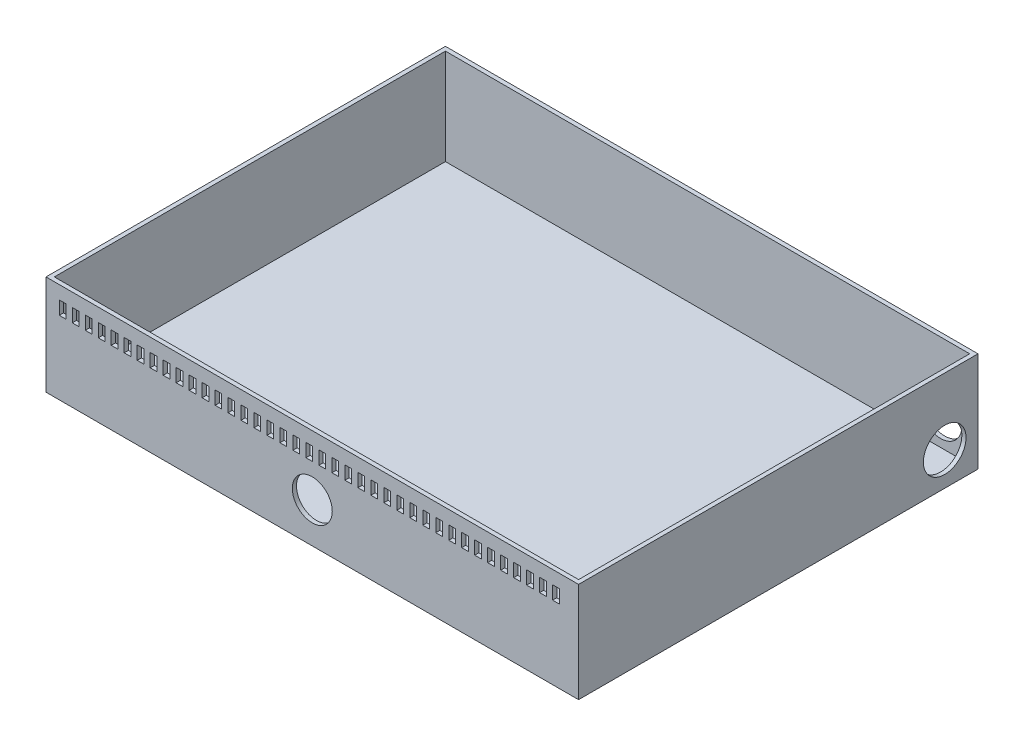
SolidWorks part; units mm, degrees
ref_plane "Front Plane" through (0, 0, 0) normal (0, 0, 1) x (1, 0, 0)
ref_plane "Top Plane" through (0, 0, 0) normal (0, 1, 0) x (1, 0, 0)
ref_plane "Right Plane" through (0, 0, 0) normal (1, 0, 0) x (0, 0, -1)
sketch "Sketch1" plane through (0, 0, 0) normal (0, 1, 0) x (1, 0, 0)
  line L1 (-101.6, -76.2) -> (101.6, -76.2)
  line L2 (-101.6, -76.2) -> (-101.6, 76.2)
  line L3 (-101.6, 76.2) -> (101.6, 76.2)
  line L4 (101.6, -76.2) -> (101.6, 76.2)
  line L5 (-101.6, -76.2) -> (101.6, 76.2) construction
  line L6 (-101.6, 76.2) -> (101.6, -76.2) construction
  point P0 (0, 0)
  dimension "D1" = 203.2
  dimension "D2" = 152.4
extrude "Boss-Extrude1" add sketch "Sketch1" along normal blind 38.1
sketch "Sketch2" plane through (0, 38.1, 0) normal (0, 1, 0) x (1, 0, 0)
  line L0 (-101.6, 76.2) -> (-101.6, -76.2) construction
  line L1 (-100.0125, -74.6125) -> (100.0125, -74.6125)
  line L2 (-100.0125, -74.6125) -> (-100.0125, 74.6125)
  line L3 (-100.0125, 74.6125) -> (100.0125, 74.6125)
  line L4 (100.0125, -74.6125) -> (100.0125, 74.6125)
  line L5 (-100.0125, -74.6125) -> (100.0125, 74.6125) construction
  line L6 (-100.0125, 74.6125) -> (100.0125, -74.6125) construction
  line L7 (101.6, 76.2) -> (-101.6, 76.2) construction
  line L8 (-101.6, -76.2) -> (101.6, -76.2) construction
  point P0 (0, 0)
  dimension "D1" = 1.5875
  dimension "D2" = 1.5875
  dimension "D3" = 1.5875
extrude "Cut-Extrude1" cut sketch "Sketch2" against normal blind 36.5125
sketch "Sketch3" plane through (0, 0, 76.2) normal (0, 0, 1) x (1, 0, 0)
  line L8 (-101.6, 38.1) -> (-101.6, 0) construction
  line L9 (-96.52, 33.02) -> (-93.98, 33.02)
  line L10 (-96.52, 33.02) -> (-96.52, 27.94)
  line L11 (-96.52, 27.94) -> (-93.98, 27.94)
  line L12 (-93.98, 33.02) -> (-93.98, 27.94)
  line L13 (-101.6, 38.1) -> (101.6, 38.1) construction
  dimension "D1" = 5.08
  dimension "D3" = 5.08
  dimension "D5" = 2.54
  dimension "D6" = 5.08
extrude "Cut-Extrude2" cut sketch "Sketch3" against normal blind 7.62
pattern_linear "LPattern1" count 39 spacing 4.953 along (1, 0, 0) of "Cut-Extrude2"
sketch "Sketch4" plane through (0, 0, 76.2) normal (0, 0, 1) x (1, 0, 0)
  line L0 (-101.6, 38.1) -> (101.6, 38.1) construction
  circle A0 centre (0, 15.24) radius 7.62
  dimension "D1" = 15.24
  dimension "D2" = 22.86
extrude "Cut-Extrude3" cut sketch "Sketch4" against normal blind 7.62
sketch "Sketch5" plane through (101.6, 0, 0) normal (1, 0, 0) x (0, 0, -1)
  line L0 (76.2, 38.1) -> (76.2, 0) construction
  line L1 (-76.2, 38.1) -> (76.2, 38.1) construction
  circle A0 centre (63.5, 12.7) radius 8.128
  dimension "D1" = 12.7
  dimension "D2" = 25.4
extrude "Cut-Extrude4" cut sketch "Sketch5" against normal blind 7.62
sketch "Sketch6" plane through (0, 0, -76.2) normal (0, 0, -1) x (-1, 0, 0)
  line L0 (-101.6, 38.1) -> (101.6, 38.1) construction
  line L1 (-101.6, 38.1) -> (-101.6, 0) construction
  circle A0 centre (-88.9, 12.7) radius 8.128
  dimension "D1" = 25.4
  dimension "D2" = 12.7
extrude "Cut-Extrude5" cut sketch "Sketch6" against normal blind 7.62
